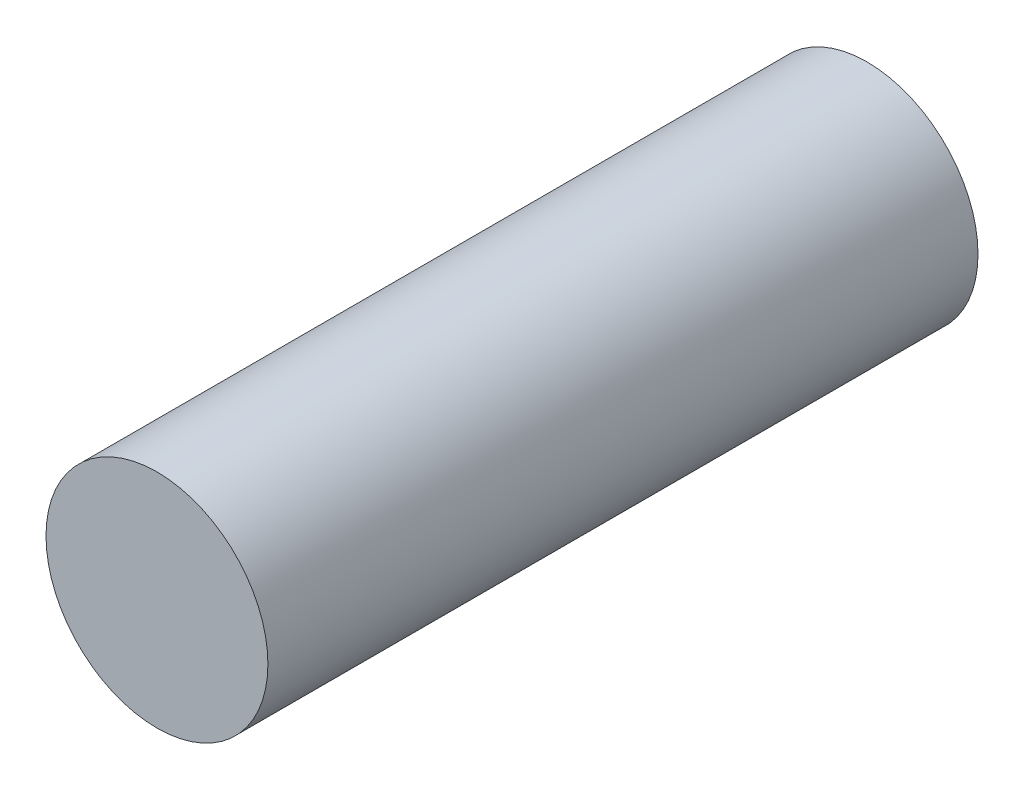
SolidWorks part; units mm, degrees
ref_plane "Front Plane" through (0, 0, 0) normal (0, 0, 1) x (1, 0, 0)
ref_plane "Top Plane" through (0, 0, 0) normal (0, 1, 0) x (1, 0, 0)
ref_plane "Right Plane" through (0, 0, 0) normal (1, 0, 0) x (0, 0, -1)
sketch "Sketch1" plane through (0, 0, 0) normal (0, 0, 1) x (1, 0, 0)
  circle A0 centre (0, 0) radius 2.5
extrude "Boss-Extrude1" add sketch "Sketch1" along normal blind 16
